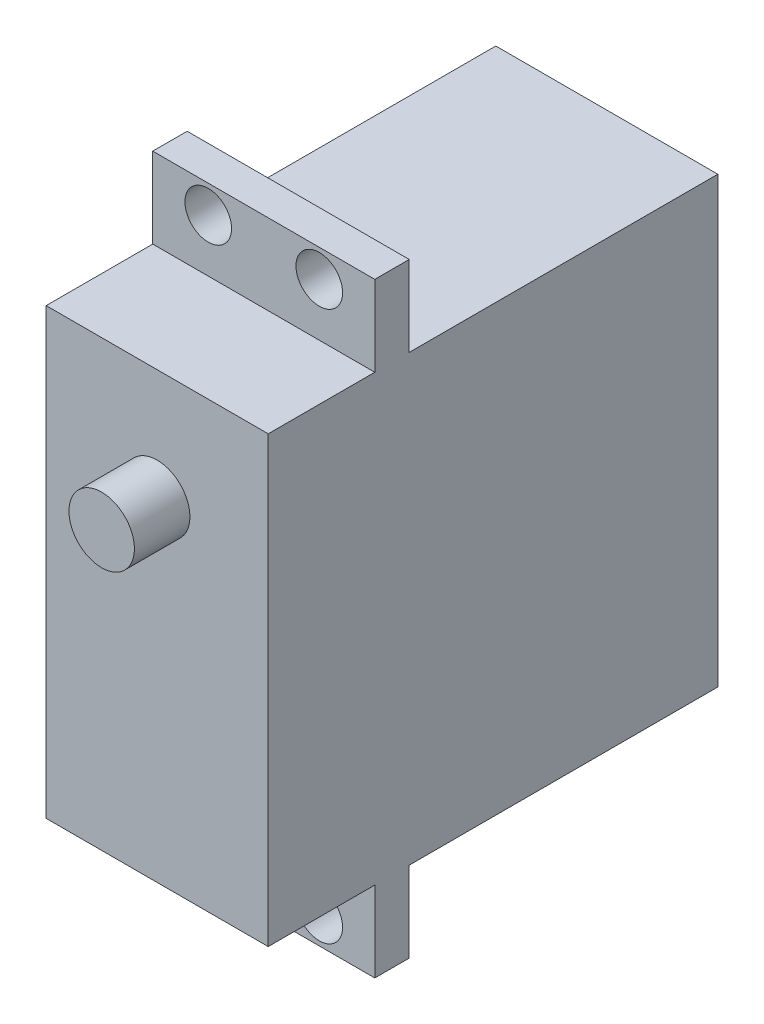
SolidWorks part; units mm, degrees
ref_plane "Front Plane" through (0, 0, 0) normal (1, 0, 0) x (0, 1, 0)
ref_plane "Top Plane" through (0, 0, 0) normal (0, 0, 1) x (0, 1, 0)
ref_plane "Right Plane" through (0, 0, 0) normal (0, 1, 0) x (-1, 0, 0)
sketch "Sketch1" plane through (0, 0, 0) normal (1, 0, 0) x (0, 1, 0)
  line L1 (-20, 20.25) -> (20, 20.25)
  line L2 (-20, 20.25) -> (-20, -20.25)
  line L3 (-20, -20.25) -> (20, -20.25)
  line L4 (20, 20.25) -> (20, -20.25)
  line L5 (-20, 20.25) -> (20, -20.25) construction
  line L6 (-20, -20.25) -> (20, 20.25) construction
  point P0 (0, 0)
  dimension "D1" = 40.5
  dimension "D2" = 40
extrude "Boss-Extrude1" add sketch "Sketch1" along normal mid plane 20
sketch "Sketch2" plane through (0, -20, 0) normal (0, -1, 0) x (1, 0, 0)
  line L0 (-10, 20.25) -> (-10, -20.25) construction
  line L1 (-10, 10.65) -> (10, 10.65)
  line L2 (-10, 10.65) -> (-10, 7.55)
  line L3 (-10, 7.55) -> (10, 7.55)
  line L4 (10, 10.65) -> (10, 7.55)
  line L5 (10, 20.25) -> (10, -20.25) construction
  line L6 (10, -20.25) -> (-10, -20.25) construction
  dimension "D1" = 27.8
  dimension "D2" = 3.1
extrude "Boss-Extrude2" add sketch "Sketch2" along normal blind 7.25
sketch "Sketch3" plane through (0, 0, 10.65) normal (0, 0, 1) x (1, 0, 0)
  line L0 (-10, -24.75) -> (-5, -24.75) construction
  line L1 (-10, -27.25) -> (-10, -20) construction
  line L2 (-5, -24.75) -> (5, -24.75) construction
  line L3 (5, -24.75) -> (10, -24.75) construction
  line L4 (10, -27.25) -> (10, -20) construction
  line L5 (10, -27.25) -> (-10, -27.25) construction
  circle A0 centre (-5, -24.75) radius 2.1
  circle A1 centre (5, -24.75) radius 2.1
  dimension "D1" = 4.2
  dimension "D2" = 10
  dimension "D3" = 2.5
extrude "Cut-Extrude1" cut sketch "Sketch3" against normal through all
mirror "Mirror1" about plane through (0, 0, 0) normal (0, 1, 0) of "Cut-Extrude1", "Boss-Extrude2"
sketch "Sketch5" plane through (0, 0, 20.25) normal (0, 0, 1) x (1, 0, 0)
  line L0 (10, 20) -> (-10, 20) construction
  circle A0 centre (0, 10) radius 2.95
  dimension "D2" = 5.9
  dimension "D1" = 10
extrude "Boss-Extrude3" add sketch "Sketch5" along normal blind 5
